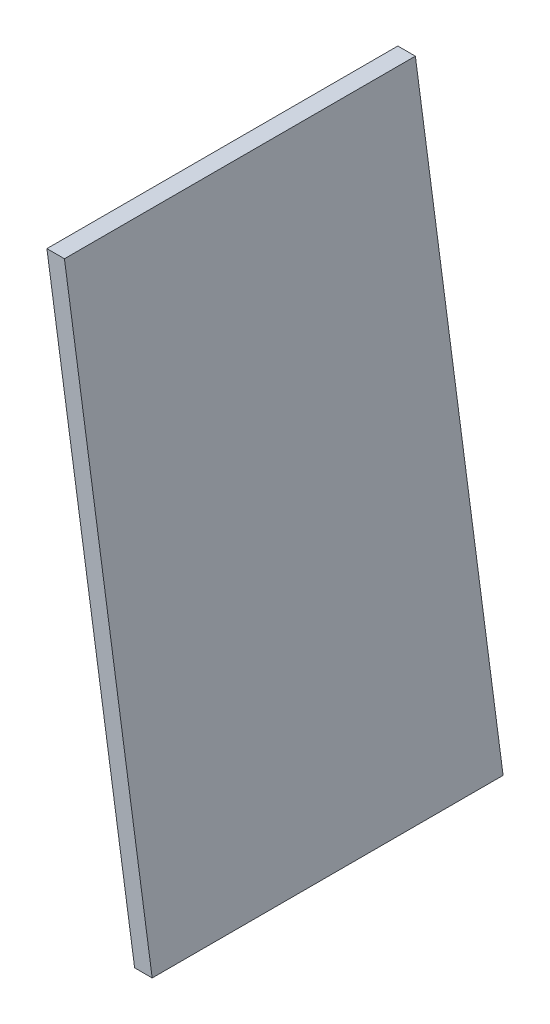
SolidWorks part; units mm, degrees
ref_plane "Alzado" through (0, 0, 0) normal (0, 0, 1) x (1, 0, 0)
ref_plane "Planta" through (0, 0, 0) normal (0, 1, 0) x (1, 0, 0)
ref_plane "Vista lateral" through (0, 0, 0) normal (1, 0, 0) x (0, 0, -1)
sketch "Croquis1" plane through (0, 0, 0) normal (0, 0, 1) x (1, 0, 0)
  line L0 (0, 0) -> (-10, 0)
  line L1 (0, 0) -> (-50, 330)
  line L2 (-10, 0) -> (-60, 330)
  line L3 (-50, 330) -> (-60, 330)
  dimension "D1" = 330
  dimension "D2" = 10
  dimension "D3" = 60
extrude "Saliente-Extruir1" add sketch "Croquis1" along normal mid plane 200
